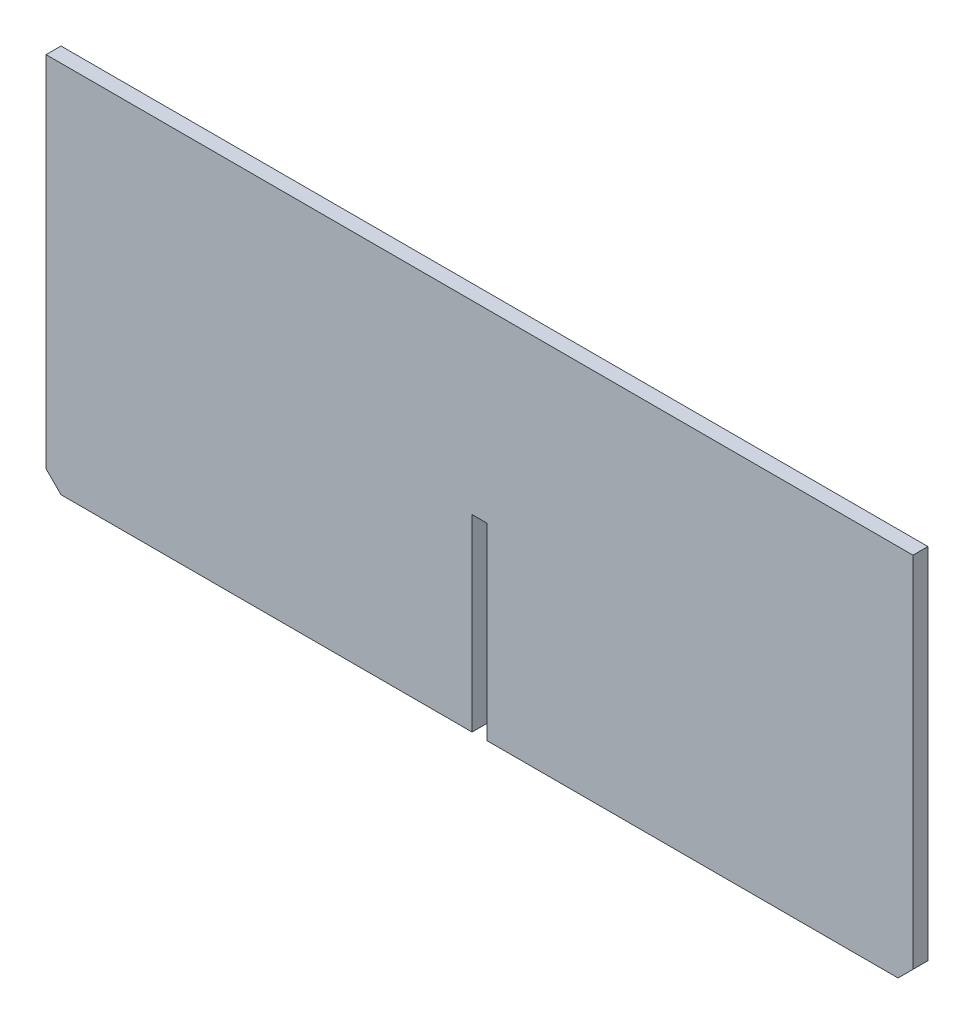
SolidWorks part; units mm, degrees
ref_plane "前视基准面" through (0, 0, 0) normal (0, 0, 1) x (1, 0, 0)
ref_plane "上视基准面" through (0, 0, 0) normal (0, 1, 0) x (1, 0, 0)
ref_plane "右视基准面" through (0, 0, 0) normal (1, 0, 0) x (0, 0, -1)
other "Configuration Table"
sketch "草图1" plane through (0, 0, 0) normal (0, 0, 1) x (1, 0, 0)
  line L1 (0, 0) -> (116, 0)
  line L2 (0, 0) -> (0, -50)
  line L3 (0, -50) -> (116, -50)
  line L4 (116, 0) -> (116, -50)
  dimension "D1" = 116
  dimension "D2" = 50
extrude "凸台-拉伸1" add sketch "草图1" along normal blind 2
chamfer "倒角1" distance 2 angle 45 2 edges at (116, -50, 1) (0, -50, 1)
sketch "草图2" plane through (0, 0, 0) normal (0, 0, -1) x (-1, 0, 0)
  line L0 (-2, -50) -> (-114, -50) construction
  line L1 (-59, -50) -> (-57, -50)
  line L2 (-59, -50) -> (-59, -24.8)
  line L3 (-59, -24.8) -> (-57, -24.8)
  line L4 (-57, -50) -> (-57, -24.8)
  line L5 (-116, 0) -> (0, 0) construction
  point P6 (-58, -24.8)
  point P9 (-58, 0)
  dimension "D1" = 0
  dimension "D2" = 2
  dimension "D3" = 25.2
extrude "切除-拉伸1" cut sketch "草图2" against normal through all
